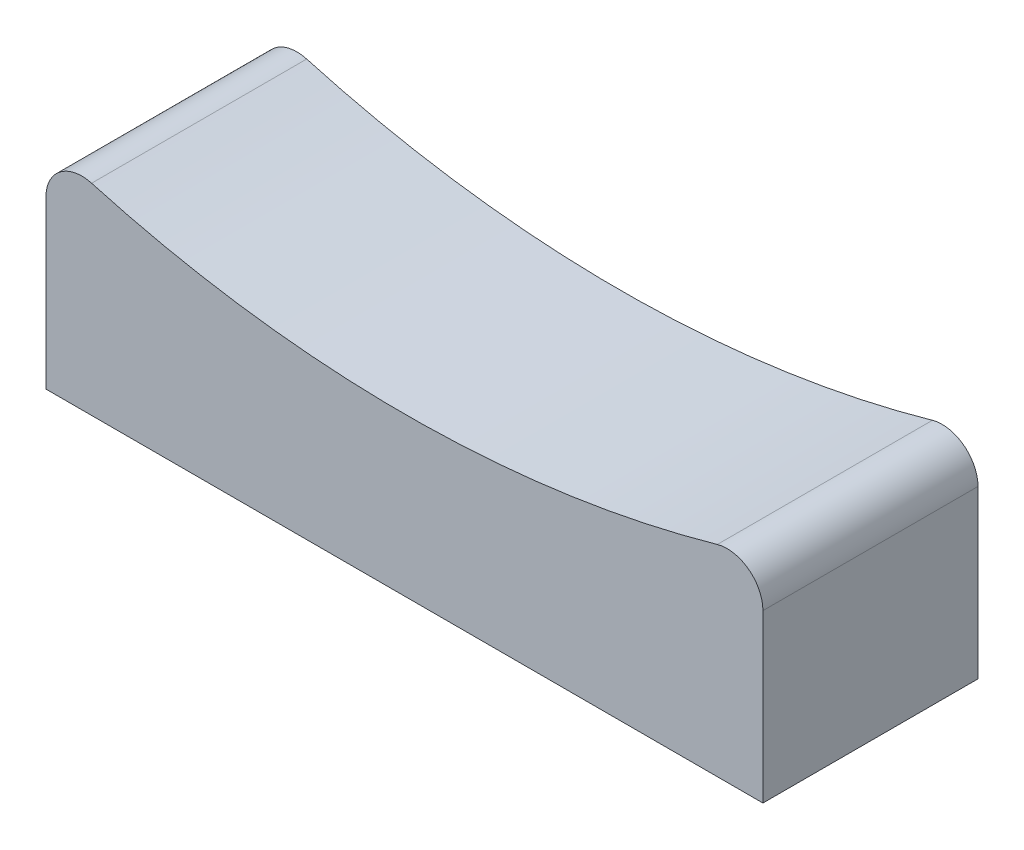
SolidWorks part; units mm, degrees
ref_plane "Front Plane" through (0, 0, 0) normal (0, 0, 1) x (1, 0, 0)
ref_plane "Top Plane" through (0, 0, 0) normal (0, 1, 0) x (1, 0, 0)
ref_plane "Right Plane" through (0, 0, 0) normal (1, 0, 0) x (0, 0, -1)
sketch "Sketch1" plane through (0, 0, 0) normal (0, 1, 0) x (1, 0, 0)
  line L1 (-50, 15) -> (50, 15)
  line L2 (-50, 15) -> (-50, -15)
  line L3 (-50, -15) -> (50, -15)
  line L4 (50, 15) -> (50, -15)
  line L5 (-50, 15) -> (50, -15) construction
  line L6 (-50, -15) -> (50, 15) construction
  point P0 (0, 0)
  dimension "D1" = 100
  dimension "D2" = 30
extrude "Boss-Extrude1" add sketch "Sketch1" along normal blind 20
sketch "Sketch2" plane through (0, 0, 15) normal (0, 0, 1) x (1, 0, 0)
  line L1 (-50, 20) -> (50, 20)
  arc A0 (-50, 20) -> (50, 20) centre (0, 172.25) ccw
  point P8 (0, 12)
  dimension "D1" = 8
extrude "Cut-Extrude1" cut sketch "Sketch2" against normal through all
fillet "Fillet1" radius 5 2 edges at (50, 20, 0) (-50, 20, 0)
sketch "Sketch3" plane through (0, 0, 0) normal (0, -1, 0) x (1, 0, 0)
  line L1 (-50, 15) -> (50, 15)
  line L2 (-50, 15) -> (-50, -15)
  line L3 (-50, -15) -> (50, -15)
  line L4 (50, 15) -> (50, -15)
extrude "Boss-Extrude2" add sketch "Sketch3" along normal blind 10
sketch "Sketch4" plane through (0, -10, 0) normal (0, -1, 0) x (1, 0, 0)
  circle A0 centre (0, 0) radius 6
  dimension "D1" = 12
extrude "Cut-Extrude2" cut sketch "Sketch4" against normal blind 5
sketch "Sketch5" plane through (0, -5, 0) normal (0, -1, 0) x (1, 0, 0)
  circle A0 centre (0, 0) radius 7.5
  dimension "D1" = 15
extrude "Cut-Extrude3" cut sketch "Sketch5" against normal blind 4.75
chamfer "Chamfer1" distance 1 angle 45 1 edges at (0, -10, -6)
